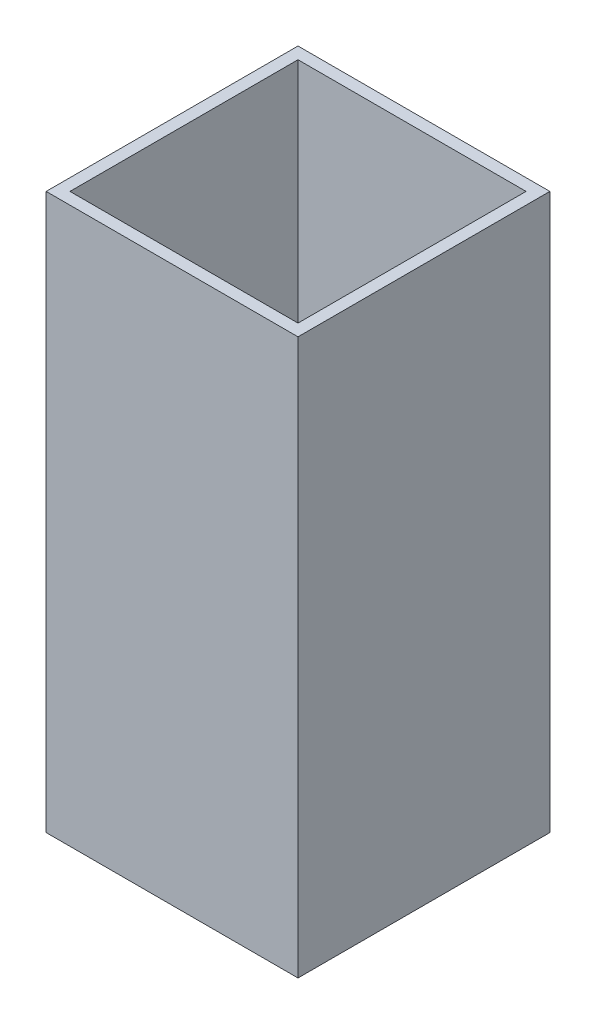
SolidWorks part; units mm, degrees
ref_plane "Front Plane" through (0, 0, 0) normal (0, 0, 1) x (1, 0, 0)
ref_plane "Top Plane" through (0, 0, 0) normal (0, 1, 0) x (1, 0, 0)
ref_plane "Right Plane" through (0, 0, 0) normal (1, 0, 0) x (0, 0, -1)
sketch "Sketch1" plane through (0, 0, 0) normal (0, 1, 0) x (1, 0, 0)
  line L0 (11.5, -11.5) -> (11.5, 11.5)
  line L1 (12.7, -12.7) -> (-12.7, -12.7)
  line L2 (12.7, -12.7) -> (12.7, 12.7)
  line L3 (12.7, 12.7) -> (-12.7, 12.7)
  line L4 (-12.7, -12.7) -> (-12.7, 12.7)
  line L5 (12.7, -12.7) -> (-12.7, 12.7) construction
  line L6 (12.7, 12.7) -> (-12.7, -12.7) construction
  line L7 (11.5, 11.5) -> (-11.5, 11.5)
  line L8 (-11.5, -11.5) -> (-11.5, 11.5)
  line L9 (11.5, -11.5) -> (-11.5, -11.5)
  point P0 (0, 0)
  dimension "D1" = 25.4
  dimension "D2" = 25.4
  dimension "D3" = 1.2
extrude "Boss-Extrude1" add sketch "Sketch1" along normal blind 56
